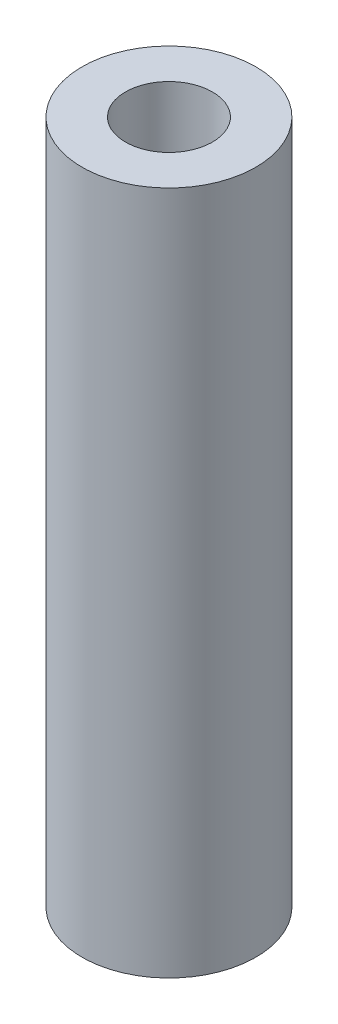
SolidWorks part; units mm, degrees
material "Delrin 2700 NC010, Low Viscosity Acetal Copolymer (SS)"
ref_plane "Front Plane" through (0, 0, 0) normal (0, 0, 1) x (1, 0, 0)
ref_plane "Top Plane" through (0, 0, 0) normal (0, 1, 0) x (1, 0, 0)
ref_plane "Right Plane" through (0, 0, 0) normal (1, 0, 0) x (0, 0, -1)
sketch "Sketch1" plane through (0, 0, 0) normal (0, 1, 0) x (1, 0, 0)
  circle A0 centre (-32.5248, 24.5388) radius 6.35
  circle A1 centre (-32.5248, 24.5388) radius 3.175
  dimension "D1" = 6.35
  dimension "D2" = 12.7
extrude "Boss-Extrude1" add sketch "Sketch1" along normal blind 49.9618
